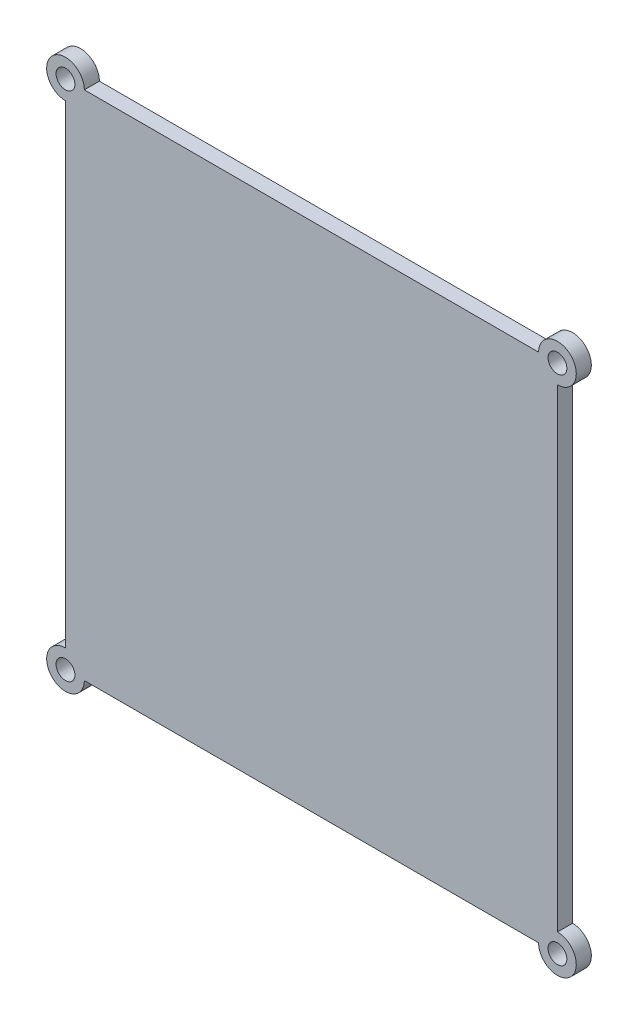
SolidWorks part; units mm, degrees
ref_plane "前视基准面" through (0, 0, 0) normal (0, 0, 1) x (1, 0, 0)
ref_plane "上视基准面" through (0, 0, 0) normal (0, 1, 0) x (1, 0, 0)
ref_plane "右视基准面" through (0, 0, 0) normal (1, 0, 0) x (0, 0, -1)
other "Configuration Table"
sketch "草图1" plane through (0, 0, 0) normal (0, 0, 1) x (1, 0, 0)
  line L0 (30.15, 33.95) -> (-30.15, 33.95)
  line L5 (30.65, -31.95) -> (-30.65, 31.95) construction
  line L6 (30.65, 31.95) -> (-30.65, -31.95) construction
  line L7 (-32.65, -31.45) -> (-32.65, 31.45)
  line L8 (30.15, -33.95) -> (-30.15, -33.95)
  line L9 (32.65, -31.45) -> (32.65, 31.45)
  arc A0 (32.65, 31.45) -> (30.15, 33.95) centre (32.65, 33.95) ccw
  arc A1 (-30.15, 33.95) -> (-32.65, 31.45) centre (-32.65, 33.95) ccw
  arc A2 (-32.65, -31.45) -> (-30.15, -33.95) centre (-32.65, -33.95) ccw
  arc A3 (30.15, -33.95) -> (32.65, -31.45) centre (32.65, -33.95) ccw
  circle A4 centre (-32.65, 33.95) radius 1.25
  circle A5 centre (32.65, 33.95) radius 1.25
  circle A6 centre (32.65, -33.95) radius 1.25
  circle A7 centre (-32.65, -33.95) radius 1.25
  point P0 (0, 0)
  dimension "D4" = 5
  dimension "D5" = 5
  dimension "D6" = 5
  dimension "D7" = 5
  dimension "D3" = 2.5
  dimension "D8" = 2.5
  dimension "D9" = 2.5
  dimension "D10" = 2.5
  dimension "D1" = 61.3
  dimension "D2" = 63.9
extrude "凸台-拉伸1" add sketch "草图1" along normal blind 2
